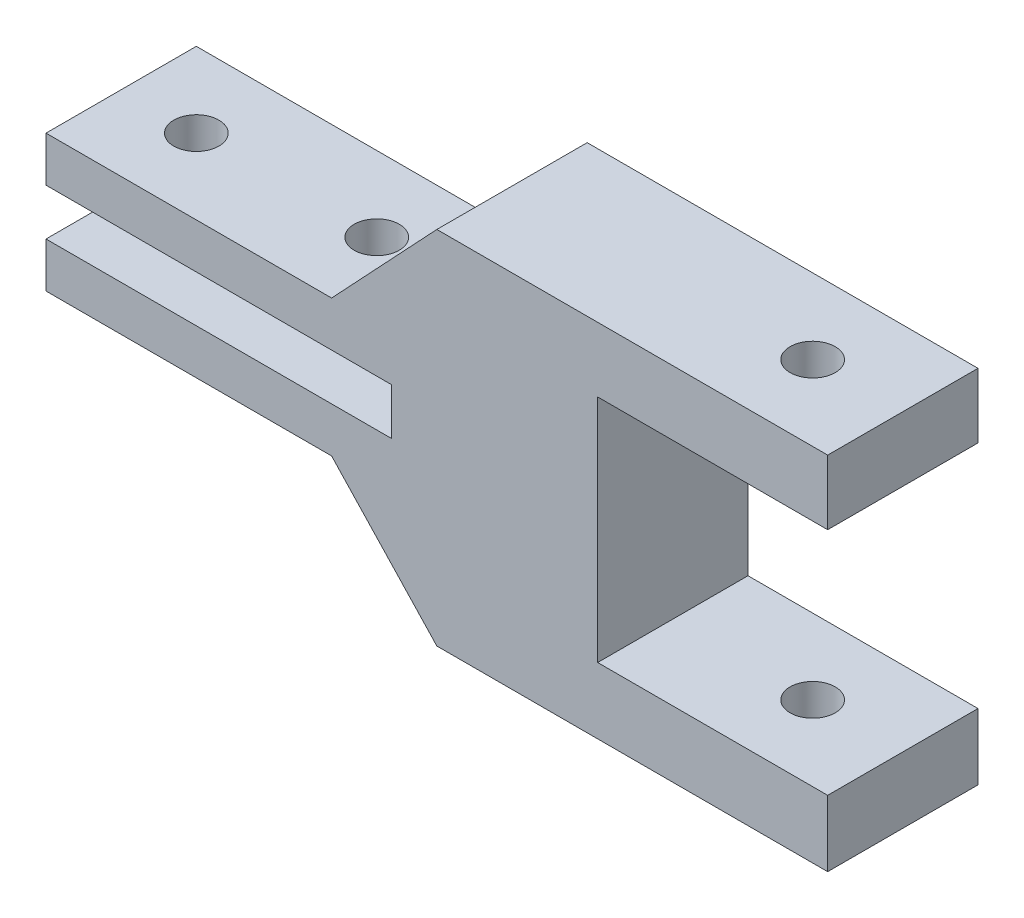
SolidWorks part; units mm, degrees
other "标注1"
sketch "草图9" plane through (-26, -12, 0) normal (-0.4913, -0.6619, -0.5661) x (-0.775, 0.0357, 0.6309)
ref_plane "前视基准面" through (0, 0, 0) normal (0, 0, 1) x (1, 0, 0)
ref_plane "上视基准面" through (0, 0, 0) normal (0, 1, 0) x (1, 0, 0)
ref_plane "右视基准面" through (0, 0, 0) normal (1, 0, 0) x (0, 0, -1)
sketch "草图1" plane through (0, 0, 0) normal (0, 0, 1) x (1, 0, 0)
  line L68 (-21.1315, 0) -> (10.2214, 0) construction
  line L78 (-26, 4.55) -> (-26, 1.55)
  line L79 (-26, 4.55) -> (-7, 4.55)
  line L82 (-26, 1.55) -> (-3, 1.55)
  line L83 (0, 4.55) -> (0, 12) construction
  line L84 (0, 12) -> (26, 12)
  line L85 (0, -12) -> (26, -12)
  line L86 (0, -4.55) -> (0, -12) construction
  line L87 (-26, -1.55) -> (-3, -1.55)
  line L90 (-26, -4.55) -> (-7, -4.55)
  line L91 (-26, -4.55) -> (-26, -1.55)
  line L92 (-3, 1.55) -> (-3, -1.55)
  line L93 (26, 12) -> (26, -12)
  line L94 (0, 1.55) -> (0, 4.55) construction
  line L95 (0, -1.55) -> (0, -4.55) construction
  line L96 (0, -12) -> (-7, -4.55)
  line L97 (0, 12) -> (-7, 4.55)
  line L98 (-7, 4.55) -> (0, 4.55) construction
  line L99 (-7, -4.55) -> (0, -4.55) construction
  dimension "D1" = 26
  dimension "D2" = 24
  dimension "D3" = 3.1
  dimension "D4" = 23
  dimension "D5" = 7
  dimension "D6" = 7
  dimension "D8" = 26
  dimension "5" = 3
extrude "凸台-拉伸1" add sketch "草图1" along normal blind 10 contours L85 L93 L84 L97 L79 L78 L82 L92 L87 L91 L90 L96
sketch "草图7" plane through (0, 4.55, 0) normal (0, 1, 0) x (1, 0, 0)
  line L0 (-21, -5) -> (-26, -5) construction
  line L2 (-26, -10) -> (-26, 0) construction
  line L3 (-21, -5) -> (-21, 0) construction
  line L4 (-26, 0) -> (-7, 0) construction
  circle A0 centre (-21, -5) radius 1.5
  circle A1 centre (-9, -5) radius 1.5
  dimension "D1" = 3
  dimension "D2" = 5
  dimension "D3" = 5
  dimension "D5" = 12
  dimension "D4" = 2
extrude "切除-拉伸5" cut sketch "草图7" against normal up to surface (9.1 mm away) up to face at (-16.5, -4.55, 5)
sketch "草图8" plane through (0, 0, 0) normal (0, 0, -1) x (-1, 0, 0)
  line L0 (-26, 12) -> (-26, -12) construction
  line L1 (-26, 7.7) -> (-10.7, 7.7)
  line L2 (-26, 7.7) -> (-26, -7.6)
  line L3 (-26, -7.6) -> (-10.7, -7.6)
  line L4 (-10.7, 7.7) -> (-10.7, -7.6)
  line L5 (0, 12) -> (-26, 12) construction
  dimension "D1" = 15.3
  dimension "D2" = 4.3
extrude "切除-拉伸6" cut sketch "草图8" against normal up to surface (10 mm away) up to face at (-6, 0, 10)
sketch "草图11" plane through (0, -12, 0) normal (0, -1, 0) x (1, 0, 0)
  line L0 (26, 10) -> (26, 0) construction
  line L1 (0, 10) -> (26, 10) construction
  circle A0 centre (20, 5) radius 1.5
  dimension "D1" = 3
  dimension "D2" = 6
  dimension "D3" = 5
extrude "切除-拉伸8" cut sketch "草图11" against normal through all
